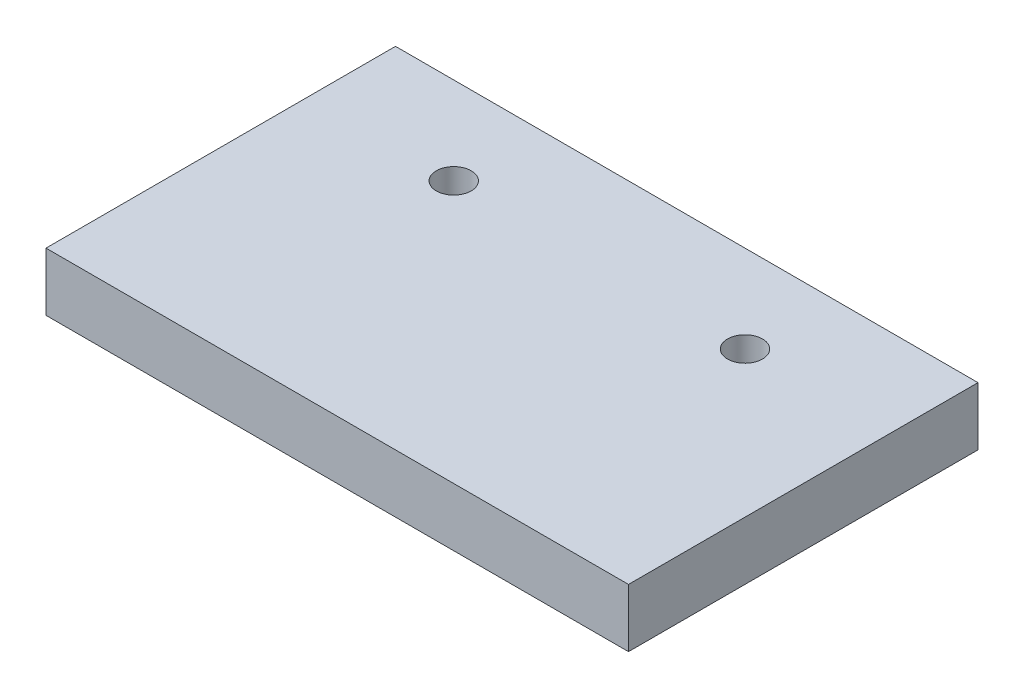
SolidWorks part; units mm, degrees
ref_plane "前视基准面" through (0, 0, 0) normal (0, 0, 1) x (1, 0, 0)
ref_plane "上视基准面" through (0, 0, 0) normal (0, 1, 0) x (1, 0, 0)
ref_plane "右视基准面" through (0, 0, 0) normal (1, 0, 0) x (0, 0, -1)
other "Configuration Table"
sketch "草图1" plane through (0, 0, 0) normal (0, 1, 0) x (1, 0, 0)
  line L1 (-50, -30) -> (50, -30)
  line L2 (-50, -30) -> (-50, 30)
  line L3 (-50, 30) -> (50, 30)
  line L4 (50, -30) -> (50, 30)
  line L5 (-50, -30) -> (50, 30) construction
  line L6 (-50, 30) -> (50, -30) construction
  point P0 (0, 0)
extrude "凸台-拉伸1" add sketch "草图1" along normal blind 10
sketch "草图2" plane through (0, 0, 0) normal (0, 1, 0) x (1, 0, 0)
  circle A0 centre (25, 15) radius 3
extrude "切除-拉伸1" cut sketch "草图2" along normal blind 20
mirror "镜向1" about plane through (0, 0, 0) normal (1, 0, 0) of "切除-拉伸1"
